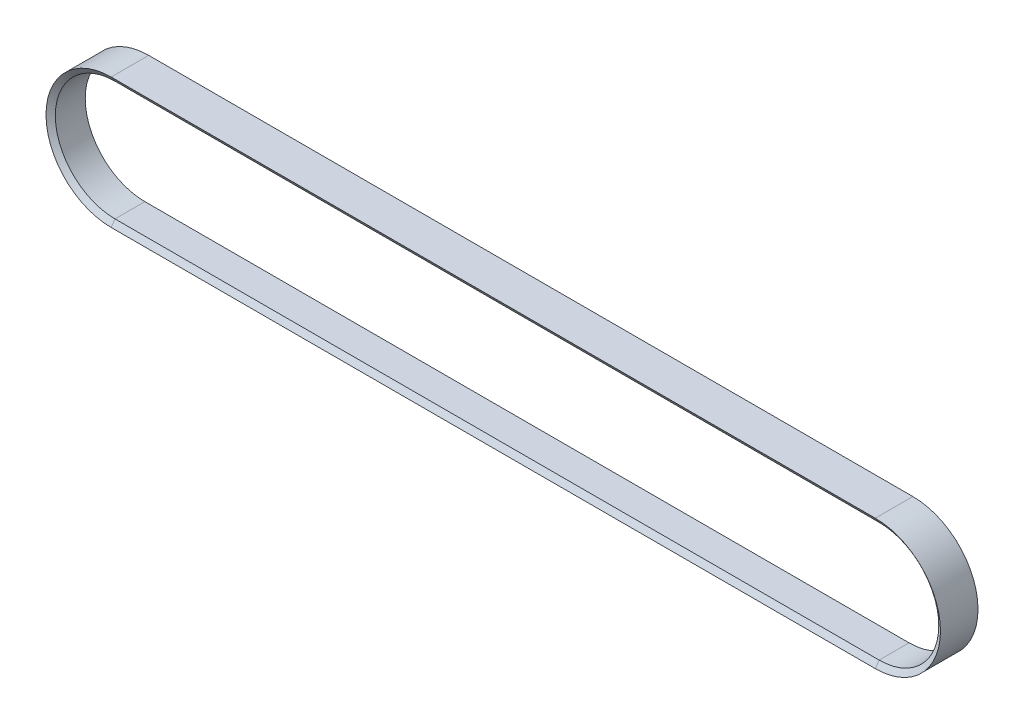
SolidWorks part; units mm, degrees
material "BUTYL"
ref_plane "Front Plane" through (0, 0, 0) normal (0, 0, 1) x (1, 0, 0)
ref_plane "Top Plane" through (0, 0, 0) normal (0, 1, 0) x (1, 0, 0)
ref_plane "Right Plane" through (0, 0, 0) normal (1, 0, 0) x (0, 0, -1)
sketch "Sketch5" plane through (0, 0, 0) normal (0, 0, 1) x (1, 0, 0)
  line L0 (-54, 0) -> (746, 0) construction
  line L1 (692, 54) -> (0, 54)
  line L2 (0, -54) -> (692, -54)
  arc A0 (0, 54) -> (0, -54) centre (0, 0) ccw
  arc A1 (692, -54) -> (692, 54) centre (692, 0) ccw
  dimension "D1" = 108
  dimension "D2" = 108
  dimension "D3" = 800
sketch "Sketch6" plane through (0, 0, 0) normal (1, 0, 0) x (0, 0, -1)
  line L0 (-13.535, 54) -> (13.535, 54)
  line L1 (0, 54) -> (0, -54) construction
  line L2 (0, 54) -> (0, -54) construction
  line L3 (13.535, 54) -> (17, 59)
  line L4 (17, 59) -> (-17, 59)
  line L5 (0, 59) -> (0, 54) construction
  line L6 (-13.535, 54) -> (-17, 59)
  dimension "D1" = 5
  dimension "D2" = 13.535
  dimension "D3" = 17
sweep "Sweep2" add profiles "Sketch6" path "Sketch5"
